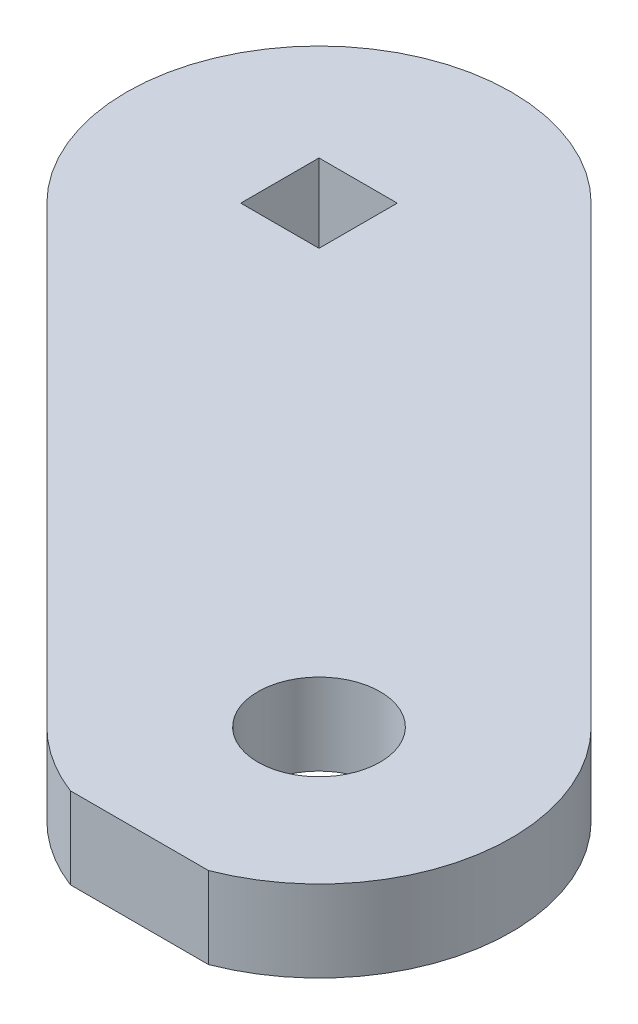
SolidWorks part; units mm, degrees
ref_plane "Front Plane" through (0, 0, 0) normal (0, 0, 1) x (1, 0, 0)
ref_plane "Top Plane" through (0, 0, 0) normal (0, 1, 0) x (1, 0, 0)
ref_plane "Right Plane" through (0, 0, 0) normal (1, 0, 0) x (0, 0, -1)
sketch "Sketch2" plane through (0, 0, 0) normal (0, 1, 0) x (1, 0, 0)
  line L0 (0, 0) -> (35.3553, -35.3553) construction
  line L1 (-3.05, 3.05) -> (3.05, 3.05)
  line L2 (-3.05, 3.05) -> (-3.05, -3.05)
  line L3 (-3.05, -3.05) -> (3.05, -3.05)
  line L4 (3.05, 3.05) -> (3.05, -3.05)
  line L5 (0, 0) -> (35.3553, 0) construction
  line L6 (-10.6066, -10.6066) -> (10.6066, 10.6066) construction
  line L7 (10.6066, 10.6066) -> (45.9619, -24.7487)
  line L8 (-10.6066, -10.6066) -> (24.7487, -45.9619)
  line L9 (29.9702, -49.3553) -> (40.7405, -49.3553)
  circle A0 centre (35.3553, -35.3553) radius 4.7625
  arc A1 (10.6066, 10.6066) -> (-10.6066, -10.6066) centre (0, 0) ccw
  arc A2 (45.9619, -24.7487) -> (24.7487, -45.9619) centre (35.3553, -35.3553) cw
  circle A3 centre (0, 7.5) radius 1.5 construction
  circle A4 centre (-7.5, 0) radius 1.5 construction
  circle A5 centre (0, 0) radius 7.5 construction
  circle A8 centre (35.3553, -35.3553) radius 37 construction
  circle A9 centre (7.5, 0) radius 1.5 construction
  circle A10 centre (0, -7.5) radius 1.5 construction
  point P4 (0, 3.05)
  point P6 (3.05, 0)
  point P13 (0, 0)
  dimension "D4" = 9.525
  dimension "D5" = 15
  dimension "D6" = 15
  dimension "D7" = 3
  dimension "D8" = 15
  dimension "D9" = 74
  dimension "D1" = 6.1
  dimension "D2" = 45
  dimension "D3" = 50
  dimension "D10" = 14
extrude "Boss-Extrude1" add sketch "Sketch2" against normal blind 6.35 contours A2 L9 L7 A1 L8 A0 L1 L4 L3 L2
